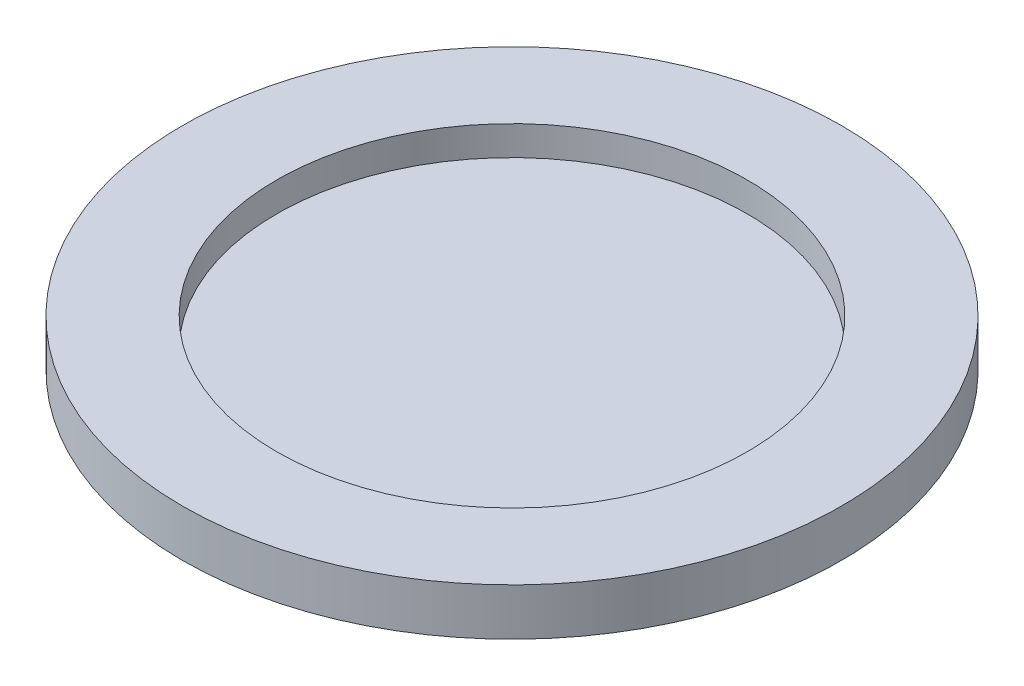
SolidWorks part; units mm, degrees
ref_plane "Plano frontal" through (0, 0, 0) normal (0, 0, 1) x (1, 0, 0)
ref_plane "Plano superior" through (0, 0, 0) normal (0, 1, 0) x (1, 0, 0)
ref_plane "Plano direito" through (0, 0, 0) normal (1, 0, 0) x (0, 0, -1)
sketch "Esboço1" plane through (0, 0, 0) normal (0, 1, 0) x (1, 0, 0)
  circle A0 centre (0, 0) radius 40
  circle A1 centre (0, 0) radius 56
extrude "Ressalto-extrusão1" add sketch "Esboço1" along normal blind 6
sketch "Esboço2" plane through (0, 0, 0) normal (0, -1, 0) x (1, 0, 0)
  circle A0 centre (0, 0) radius 56
extrude "Ressalto-extrusão2" add sketch "Esboço2" along normal blind 2
sketch "Esboço3" plane through (0, 0, 0) normal (0, 1, 0) x (1, 0, 0)
  circle A0 centre (0, 0) radius 40
extrude "Ressalto-extrusão3" add sketch "Esboço3" along normal blind 1
